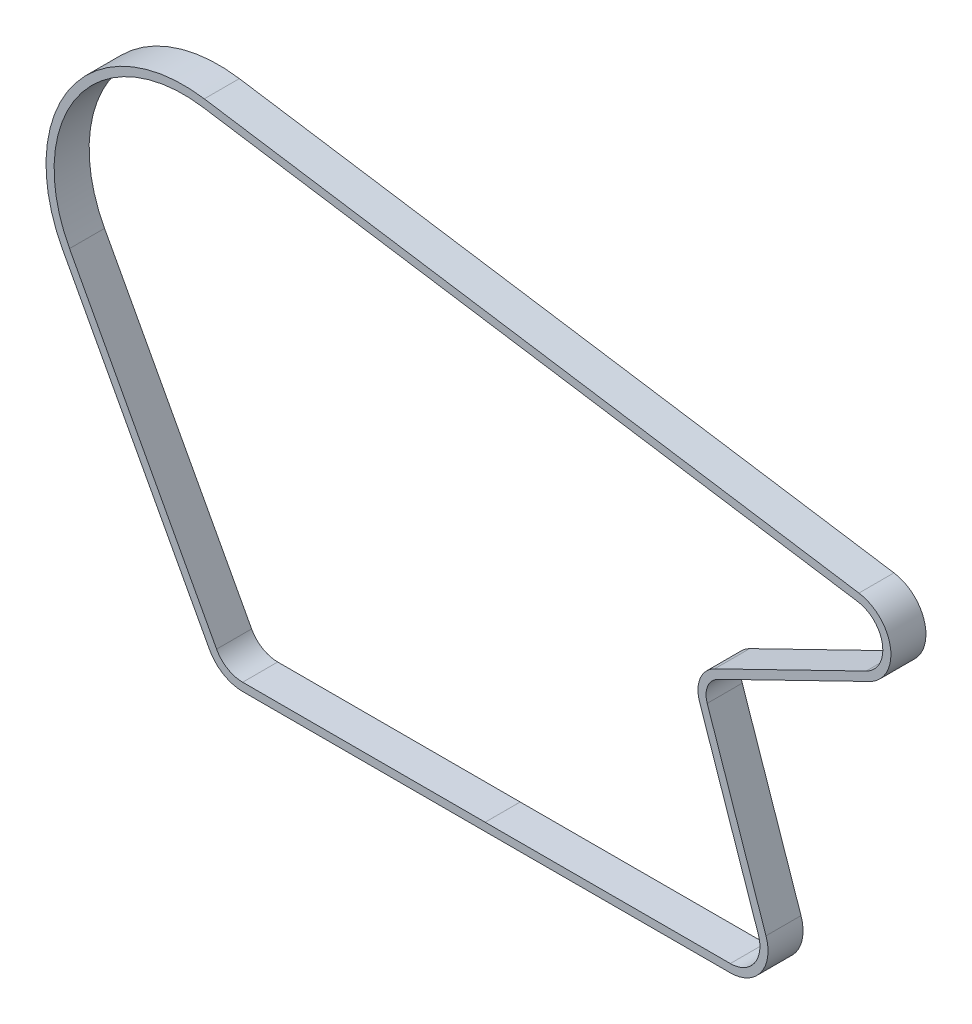
SolidWorks part; units mm, degrees
ref_plane "Front Plane" through (0, 0, 0) normal (0, 0, 1) x (1, 0, 0)
ref_plane "Top Plane" through (0, 0, 0) normal (0, 1, 0) x (1, 0, 0)
ref_plane "Right Plane" through (0, 0, 0) normal (1, 0, 0) x (0, 0, -1)
sketch "Sketch2" plane through (0, 0, 0) normal (0, 0, 1) x (1, 0, 0)
  line L0 (0, 0) -> (1, 0) construction
  line L1 (0, 0) -> (0, 1) construction
  line L2 (4.8186, -9.8884) -> (-51.4299, -37.2979)
  line L3 (-57.02, -50.7445) -> (-35.2052, -114.5602)
  line L4 (-45.6056, -129.1183) -> (-136.5986, -129.1864)
  line L5 (-136.6068, -129.1864) -> (-226.6023, -129.1864)
  line L6 (-236.2897, -123.3974) -> (-290.8734, -21.9254)
  line L7 (-241.302, 48.2554) -> (1.6727, 10.8721)
  arc A0 (1.6727, 10.8721) -> (4.8186, -9.8884) centre (0, 0) cw
  arc A1 (-51.4299, -37.2979) -> (-57.02, -50.7445) centre (-46.6113, -47.1864) ccw
  arc A2 (-35.2052, -114.5602) -> (-45.6056, -129.1183) centre (-45.6138, -118.1183) cw
  arc A3 (-136.5986, -129.1864) -> (-136.6068, -129.1864) centre (-136.6068, -118.1864) cw
  arc A4 (-226.6023, -129.1864) -> (-236.2897, -123.3974) centre (-226.6023, -118.1864) cw
  arc A5 (-290.8734, -21.9254) -> (-241.302, 48.2554) centre (-248.6012, 0.8136) cw
extrude "Extrude-Thin1" add sketch "Sketch2" along normal blind 10 and the other way blind 3 thin thin type one direction wall 3
